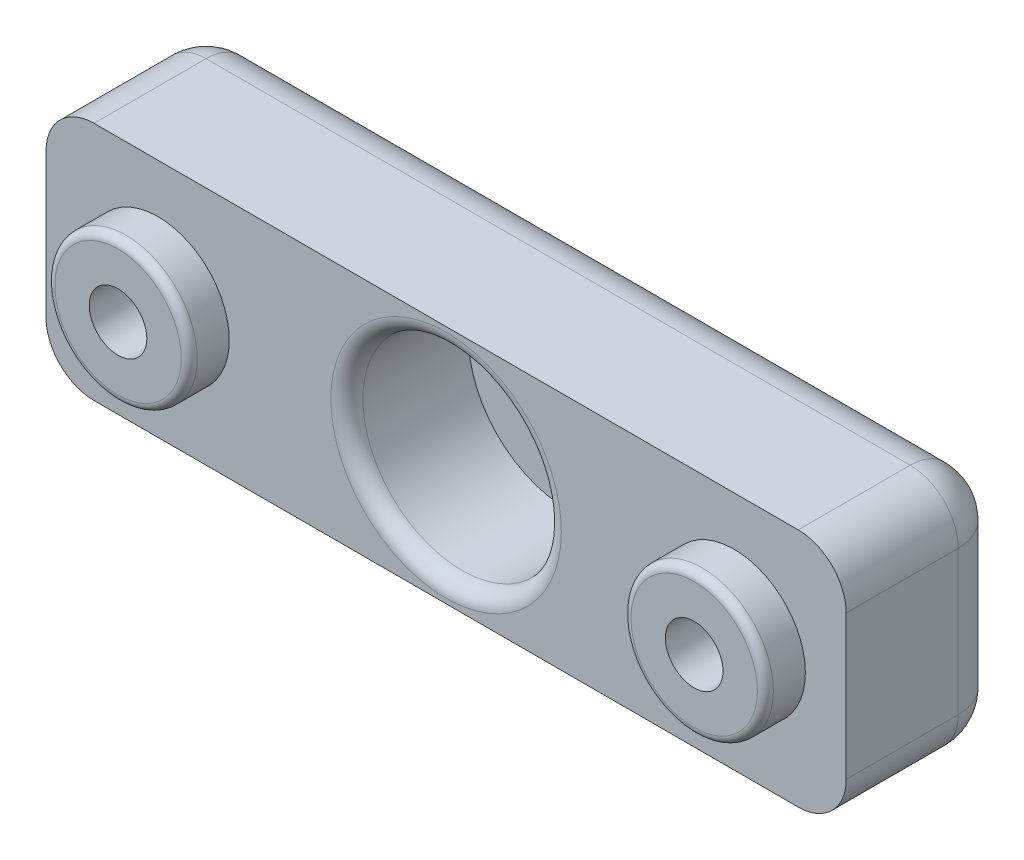
SolidWorks part; units mm, degrees
ref_plane "Alzado" through (0, 0, 0) normal (0, 0, 1) x (1, 0, 0)
ref_plane "Planta" through (0, 0, 0) normal (0, 1, 0) x (1, 0, 0)
ref_plane "Vista lateral" through (0, 0, 0) normal (1, 0, 0) x (0, 0, -1)
sketch "Croquis1" plane through (0, 0, 0) normal (0, 0, 1) x (1, 0, 0)
  line L1 (-27.43, 16.0979) -> (22.57, 16.0979)
  line L2 (-27.43, 16.0979) -> (-27.43, 1.0979)
  line L3 (-27.43, 1.0979) -> (22.57, 1.0979)
  line L4 (22.57, 16.0979) -> (22.57, 1.0979)
  dimension "D1" = 50
  dimension "D2" = 15
extrude "Saliente-Extruir1" add sketch "Croquis1" along normal blind 10
sketch "Croquis2" plane through (0, 0, 10) normal (0, 0, 1) x (1, 0, 0)
  line L0 (-27.43, 1.0979) -> (22.57, 16.0979) construction
  line L1 (22.57, 16.0979) -> (-27.43, 16.0979) construction
  line L2 (22.57, 1.0979) -> (22.57, 16.0979) construction
  circle A0 centre (-2.43, 8.5979) radius 6.2
  circle A1 centre (-20.43, 8.5979) radius 4.45
  circle A2 centre (15.57, 8.5979) radius 4.45
  dimension "D1" = 12.4
  dimension "D2" = 8.9
  dimension "D3" = 8.9
  dimension "D4" = 18
  dimension "D5" = 18
extrude "Saliente-Extruir2" add sketch "Croquis2" along normal blind 2.5
sketch "Croquis3" plane through (0, 0, 12.5) normal (0, 0, 1) x (1, 0, 0)
  circle A1 centre (-2.43, 8.5979) radius 6.2
  circle A2 centre (-2.43, 8.5979) radius 6.2
  dimension "D1" = 0
extrude "Cortar-Extruir1" cut sketch "Croquis3" against normal blind 10.1
sketch "Croquis4" plane through (0, 0, 12.5) normal (0, 0, 1) x (1, 0, 0)
  circle A0 centre (-20.43, 8.5979) radius 1.8
  circle A1 centre (15.57, 8.5979) radius 1.8
  dimension "D1" = 3.6
  dimension "D2" = 3.6
extrude "Cortar-Extruir2" cut sketch "Croquis4" against normal blind 15.5
sketch "Croquis5" plane through (0, 0, 0) normal (0, 0, -1) x (-1, 0, 0)
  line L1 (-12.0482, 8.5979) -> (-13.8091, 11.6479)
  line L2 (-13.8091, 11.6479) -> (-17.3309, 11.6479)
  line L3 (-17.3309, 11.6479) -> (-19.0918, 8.5979)
  line L4 (-19.0918, 8.5979) -> (-17.3309, 5.5479)
  line L5 (-17.3309, 5.5479) -> (-13.8091, 5.5479)
  line L6 (-13.8091, 5.5479) -> (-12.0482, 8.5979)
  line L7 (23.9518, 8.5979) -> (22.1909, 11.6479)
  line L8 (22.1909, 11.6479) -> (18.6691, 11.6479)
  line L9 (18.6691, 11.6479) -> (16.9082, 8.5979)
  line L10 (16.9082, 8.5979) -> (18.6691, 5.5479)
  line L11 (18.6691, 5.5479) -> (22.1909, 5.5479)
  line L12 (22.1909, 5.5479) -> (23.9518, 8.5979)
  circle A0 centre (-15.57, 8.5979) radius 3.05 construction
  circle A1 centre (20.43, 8.5979) radius 3.05 construction
  dimension "D1" = 6.1
  dimension "D2" = 6.1
extrude "Cortar-Extruir3" cut sketch "Croquis5" against normal blind 3.5
fillet "Redondeo1" radius 3 8 edges at (-2.43, 1.0979, 0) (22.57, 1.0979, 5) (22.57, 16.0979, 5) (22.57, 8.5979, 0) (-27.43, 1.0979, 5) (-27.43, 8.5979, 0) (-27.43, 16.0979, 5) (-2.43, 16.0979, 0)
fillet "Redondeo2" radius 1 1 edges at (3.77, 8.5979, 10)
fillet "Redondeo3" radius 0.5 2 edges at (20.02, 8.5979, 12.5) (-15.98, 8.5979, 12.5)
